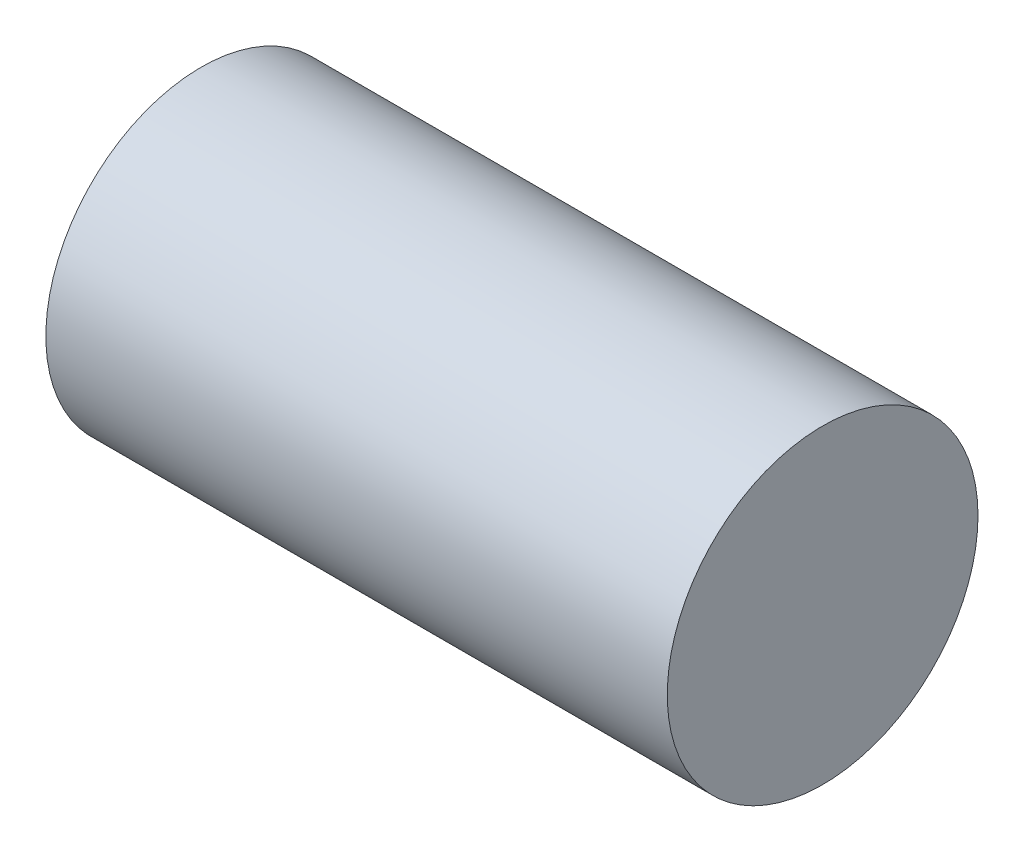
SolidWorks part; units mm, degrees
ref_plane "Front Plane" through (0, 0, 0) normal (0, 0, 1) x (1, 0, 0)
ref_plane "Top Plane" through (0, 0, 0) normal (0, 1, 0) x (1, 0, 0)
ref_plane "Right Plane" through (0, 0, 0) normal (1, 0, 0) x (0, 0, -1)
sketch "Sketch1" plane through (0, 0, 0) normal (1, 0, 0) x (0, 0, -1)
  circle A0 centre (0, 0) radius 7.5
  dimension "D1" = 15
extrude "Boss-Extrude1" add sketch "Sketch1" along normal blind 30
